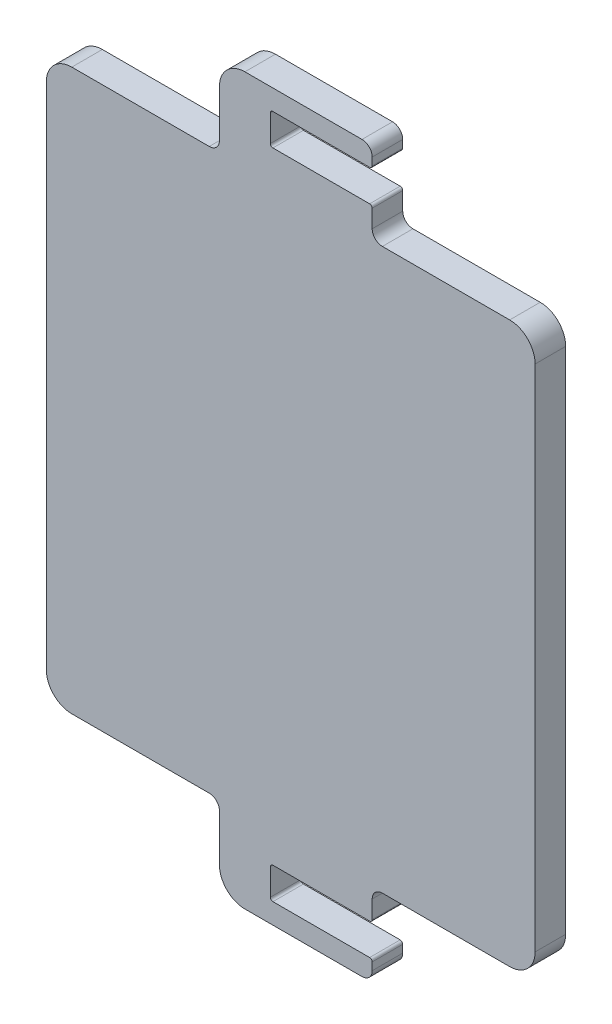
SolidWorks part; units mm, degrees
ref_plane "Alzado" through (0, 0, 0) normal (0, 0, 1) x (1, 0, 0)
ref_plane "Planta" through (0, 0, 0) normal (0, 1, 0) x (1, 0, 0)
ref_plane "Vista lateral" through (0, 0, 0) normal (1, 0, 0) x (0, 0, -1)
sketch "Croquis1" plane through (0, 0, 0) normal (0, 0, 1) x (1, 0, 0)
  line L0 (-9.0425, 0) -> (8.7011, 0) construction
  line L2 (-24, 25) -> (-24, -25)
  line L4 (24, 25) -> (24, -25)
  line L5 (-24, 27.5) -> (24, -27.5) construction
  line L6 (-24, -27.5) -> (24, 27.5) construction
  line L14 (-21.5, 27.5) -> (-7, 27.5)
  line L15 (8, 27.5) -> (21.5, 27.5)
  line L23 (8, -27.5) -> (21.5, -27.5)
  line L24 (-7, -27.5) -> (-21.5, -27.5)
  line L25 (-7, 27.5) -> (-7, 33.1)
  line L26 (-4.5, 35.6) -> (8, 35.6)
  line L27 (8, 35.6) -> (8, 33.6)
  line L28 (8, 33.6) -> (-2, 33.6)
  line L29 (-2, 33.6) -> (-2, 30.5)
  line L30 (-2, 30.5) -> (8, 30.5)
  line L31 (8, 30.5) -> (8, 27.5)
  line L32 (8, -30.5) -> (8, -27.5)
  line L33 (-2, -30.5) -> (8, -30.5)
  line L34 (-2, -33.6) -> (-2, -30.5)
  line L35 (8, -33.6) -> (-2, -33.6)
  line L36 (8, -35.6) -> (8, -33.6)
  line L37 (-4.5, -35.6) -> (8, -35.6)
  line L38 (-7, -27.5) -> (-7, -33.1)
  arc A2 (-24, -25) -> (-21.5, -27.5) centre (-21.5, -25) ccw
  arc A3 (21.5, -27.5) -> (24, -25) centre (21.5, -25) ccw
  arc A4 (21.5, 27.5) -> (24, 25) centre (21.5, 25) cw
  arc A5 (-21.5, 27.5) -> (-24, 25) centre (-21.5, 25) ccw
  arc A6 (-7, 33.1) -> (-4.5, 35.6) centre (-4.5, 33.1) cw
  arc A7 (-7, -33.1) -> (-4.5, -35.6) centre (-4.5, -33.1) ccw
  point P0 (0, 0)
  point P8 (-7, 27.5)
  point P19 (8.5, 35.6)
  point P42 (-7, 35.6)
  dimension "D9" = 48
  dimension "D10" = 2.5
  dimension "D8" = 2.5
  dimension "D1" = 55
  dimension "D2" = 10
  dimension "D3" = 10
  dimension "D4" = 2
  dimension "D5" = 3.1
  dimension "D6" = 3
  dimension "D7" = 15
  dimension "D11" = 8.1
extrude "Saliente-Extruir1" add sketch "Croquis1" along normal blind 3 contours L14 L25 A6 L26 L27 L28 L29 L30 L31 L15 A4 L4 A3 L23 L32 L33 L34 L35 L36 L37 A7 L38 L24 A2 L2 A5
fillet "Redondeo1" radius 1 6 edges at (8, 35.6, 1.5) (8, 27.5, 1.5) (-7, 27.5, 1.5) (-7, -27.5, 1.5) (8, -35.6, 1.5) (8, -27.5, 1.5)
fillet "Redondeo2" radius 0.25 8 edges at (8, -30.5, 1.5) (-2, -30.5, 1.5) (-2, -33.6, 1.5) (8, -33.6, 1.5) (-2, 30.5, 1.5) (-2, 33.6, 1.5) (8, 33.6, 1.5) (8, 30.5, 1.5)
